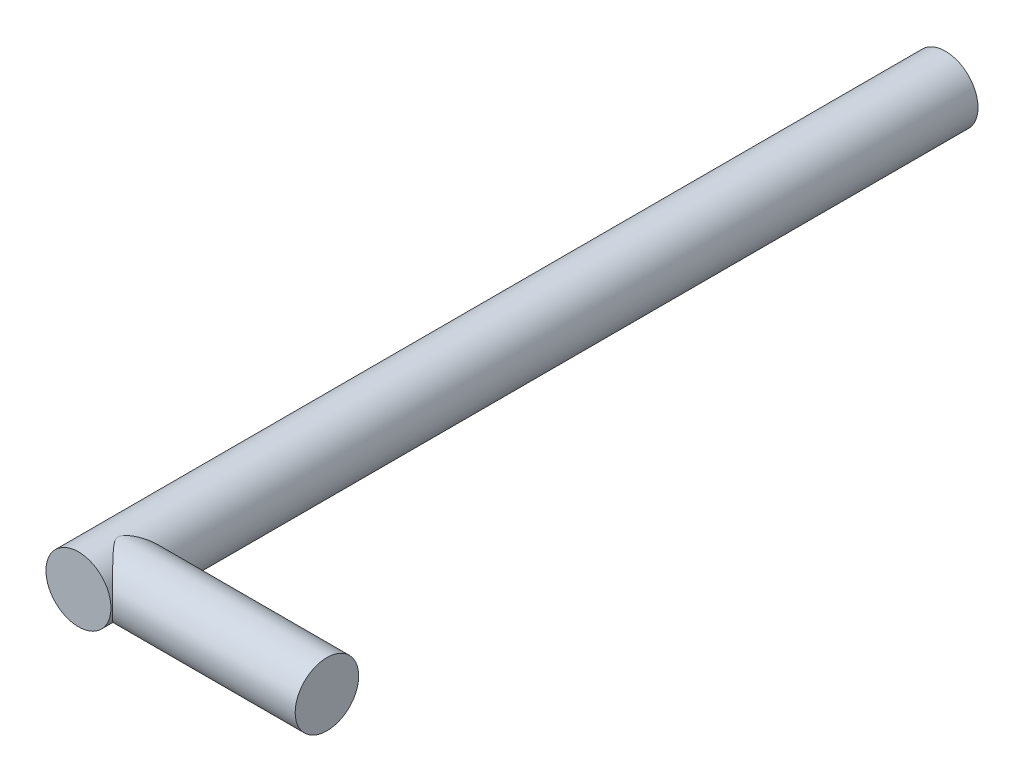
SolidWorks part; units mm, degrees
ref_plane "Front Plane" through (0, 0, 0) normal (0, 0, 1) x (1, 0, 0)
ref_plane "Top Plane" through (0, 0, 0) normal (0, 1, 0) x (1, 0, 0)
ref_plane "Right Plane" through (0, 0, 0) normal (1, 0, 0) x (0, 0, -1)
sketch "Sketch3" plane through (0, 0, 0) normal (0, 0, 1) x (1, 0, 0)
  circle A0 centre (-77.0477, 20.4872) radius 1.5
extrude "Boss-Extrude1" add sketch "Sketch3" along normal blind 40
sketch "Sketch4" plane through (0, 0, 40) normal (0, 0, 1) x (1, 0, 0)
  line L0 (-76.976, 23.9729) -> (-76.976, 21.9855)
  line L1 (-76.976, 21.9855) -> (-77.1194, 21.9855)
  line L2 (-77.1194, 21.9855) -> (-77.1194, 23.9729)
  line L3 (-77.1194, 23.9729) -> (-76.976, 23.9729)
  line L5 (-77.1194, 23.9729) -> (-76.976, 23.9729)
  line L6 (-77.1194, 23.9729) -> (-77.1194, 21.9855)
  line L7 (-77.1194, 21.9855) -> (-76.976, 21.9855)
  line L8 (-76.976, 23.9729) -> (-76.976, 21.9855)
  circle A0 centre (-77.0477, 20.4872) radius 1.5 construction
extrude "Extrude-Thin1" add sketch "Sketch4" along normal blind 10 thin contours L2
sketch "Sketch7" plane through (-77.1194, 0, 0) normal (-1, 0, 0) x (0, 0, 1)
  circle A0 centre (38.4649, 20.4937) radius 1.465
extrude "Boss-Extrude4" add sketch "Sketch7" against normal blind 10 contours A0
sketch "Sketch9" plane through (-77.1194, 0, 0) normal (-1, 0, 0) x (0, 0, 1)
  line L1 (40, 23.9729) -> (51.2522, 23.9729)
  line L2 (40, 23.9729) -> (40, 20.844)
  line L3 (40, 20.844) -> (51.2522, 20.844)
  line L4 (51.2522, 23.9729) -> (51.2522, 20.844)
extrude "Cut-Extrude1" cut sketch "Sketch9" against normal through all
